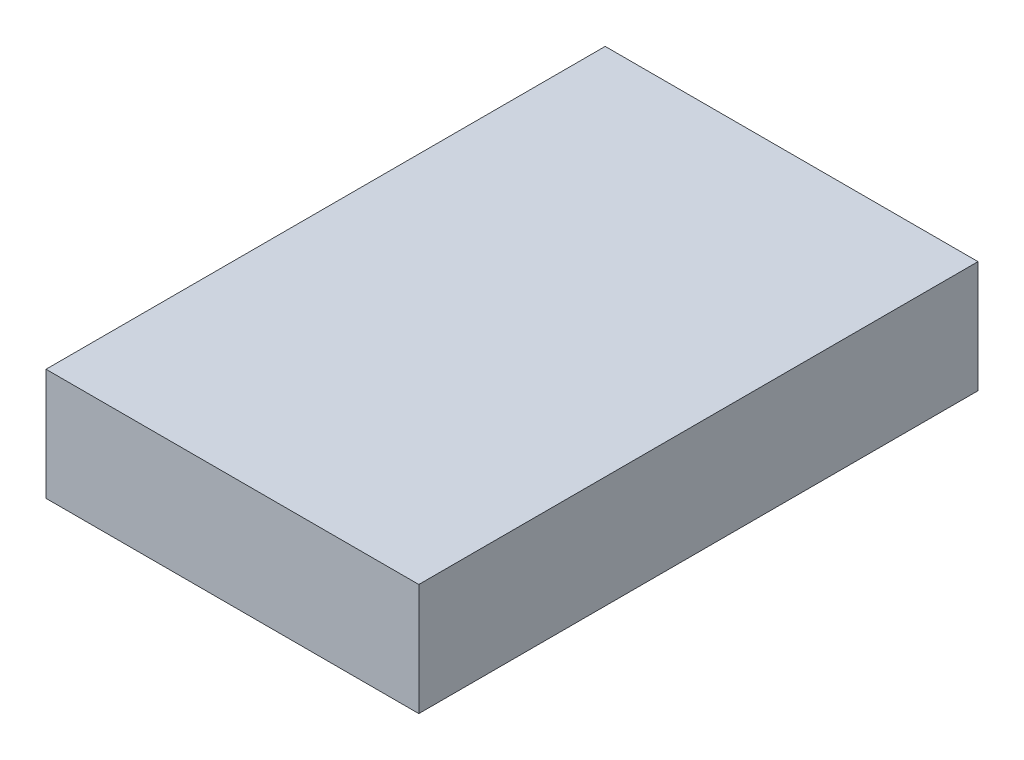
SolidWorks part; units mm, degrees
ref_plane "Front Plane" through (0, 0, 0) normal (0, 0, 1) x (1, 0, 0)
ref_plane "Top Plane" through (0, 0, 0) normal (0, 1, 0) x (1, 0, 0)
ref_plane "Right Plane" through (0, 0, 0) normal (1, 0, 0) x (0, 0, -1)
sketch "Sketch1" plane through (0, 0, 0) normal (0, 1, 0) x (1, 0, 0)
  line L1 (-25, -37.5) -> (25, -37.5)
  line L2 (-25, -37.5) -> (-25, 37.5)
  line L3 (-25, 37.5) -> (25, 37.5)
  line L4 (25, -37.5) -> (25, 37.5)
  line L5 (-25, -37.5) -> (25, 37.5) construction
  line L6 (-25, 37.5) -> (25, -37.5) construction
  point P0 (0, 0)
  dimension "D1" = 50
  dimension "D2" = 75
extrude "Boss-Extrude1" add sketch "Sketch1" along normal blind 15
